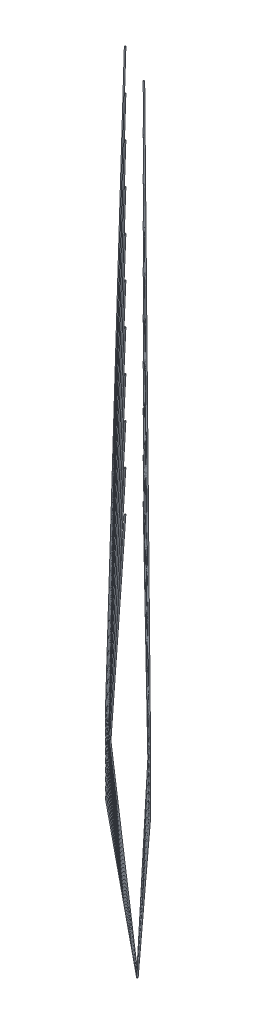
SolidWorks part; units mm, degrees
ref_plane "Front Plane" through (0, 0, 0) normal (0, 0, 1) x (1, 0, 0)
ref_plane "Top Plane" through (0, 0, 0) normal (0, 1, 0) x (1, 0, 0)
ref_plane "Right Plane" through (0, 0, 0) normal (1, 0, 0) x (0, 0, -1)
sketch3d "3DSketch1"
  line L0 (0, -235, 30) -> (-30, -45, 25)
  line L1 (-30, -45, 25) -> (-10, 300, 0)
sketch3d "3DSketch2"
  line L0 (0, -235, 30) -> (-30, -34, 25)
  line L1 (-30, -34, 25) -> (-10, 356, 0)
sketch3d "3DSketch3"
  line L0 (0, -235, 30) -> (-30, -23, 25)
  line L1 (-30, -23, 25) -> (-10, 412, 0)
sketch3d "3DSketch4"
  line L0 (0, -235, 30) -> (-30, -12, 25)
  line L1 (-30, -12, 25) -> (-10, 468, 0)
sketch3d "3DSketch5"
  line L0 (0, -235, 30) -> (-30, -1, 25)
  line L1 (-30, -1, 25) -> (-10, 524, 0)
sketch3d "3DSketch6"
  line L0 (0, -235, 30) -> (-30, 10, 25)
  line L1 (-30, 10, 25) -> (-10, 580, 0)
sketch3d "3DSketch7"
  line L0 (0, -235, 30) -> (-30, 21, 25)
  line L1 (-30, 21, 25) -> (-10, 636, 0)
sketch3d "3DSketch8"
  line L0 (0, -235, 30) -> (-30, 32, 25)
  line L1 (-30, 32, 25) -> (-10, 692, 0)
sketch3d "3DSketch9"
  line L0 (0, -235, 30) -> (-30, 43, 25)
  line L1 (-30, 43, 25) -> (-10, 748, 0)
sketch3d "3DSketch10"
  line L0 (0, -235, 30) -> (-30, 54, 25)
  line L1 (-30, 54, 25) -> (-10, 804, 0)
sketch3d "3DSketch11"
  line L0 (0, -235, 30) -> (-30, 65, 25)
  line L1 (-30, 65, 25) -> (-10, 860, 0)
sketch3d "3DSketch12"
  line L0 (0, -235, 30) -> (30, -39.5, 25)
  line L1 (30, -39.5, 25) -> (10, 328, 0)
sketch3d "3DSketch13"
  line L0 (0, -235, 30) -> (30, -28.5, 25)
  line L1 (30, -28.5, 25) -> (10, 384, 0)
sketch3d "3DSketch14"
  line L0 (0, -235, 30) -> (30, -17.5, 25)
  line L1 (30, -17.5, 25) -> (10, 440, 0)
sketch3d "3DSketch15"
  line L0 (0, -235, 30) -> (30, -6.5, 25)
  line L1 (30, -6.5, 25) -> (10, 496, 0)
sketch3d "3DSketch16"
  line L0 (0, -235, 30) -> (30, 4.5, 25)
  line L1 (30, 4.5, 25) -> (10, 552, 0)
sketch3d "3DSketch17"
  line L0 (0, -235, 30) -> (30, 15.5, 25)
  line L1 (30, 15.5, 25) -> (10, 608, 0)
sketch3d "3DSketch18"
  line L0 (0, -235, 30) -> (30, 26.5, 25)
  line L1 (30, 26.5, 25) -> (10, 664, 0)
sketch3d "3DSketch19"
  line L0 (0, -235, 30) -> (30, 37.5, 25)
  line L1 (30, 37.5, 25) -> (10, 720, 0)
sketch3d "3DSketch20"
  line L0 (0, -235, 30) -> (30, 48.5, 25)
  line L1 (30, 48.5, 25) -> (10, 776, 0)
sketch3d "3DSketch21"
  line L0 (0, -235, 30) -> (30, 59.5, 25)
  line L1 (30, 59.5, 25) -> (10, 832, 0)
sketch3d "3DSketch22"
  line L0 (0, -250, 12) -> (-30, -45, 25)
  line L1 (-30, -45, 25) -> (-13, 300, 16)
sweep "Sweep22" add path "3DSketch22" circular profile diameter 1.5 parameters "D3"=1.5
sketch3d "3DSketch23"
  line L0 (0, -250, 12) -> (-30, -34, 25)
  line L1 (-30, -34, 25) -> (-13, 356, 16)
sweep "Sweep23" add path "3DSketch23" circular profile diameter 1.5 parameters "D3"=1.5
sketch3d "3DSketch24"
  line L0 (0, -250, 12) -> (-30, -23, 25)
  line L1 (-30, -23, 25) -> (-13, 412, 16)
sweep "Sweep24" add path "3DSketch24" circular profile diameter 1.5 parameters "D3"=1.5
sketch3d "3DSketch25"
  line L0 (0, -250, 12) -> (-30, -12, 25)
  line L1 (-30, -12, 25) -> (-13, 468, 16)
sweep "Sweep25" add path "3DSketch25" circular profile diameter 1.5 parameters "D3"=1.5
sketch3d "3DSketch26"
  line L0 (0, -250, 12) -> (-30, -1, 25)
  line L1 (-30, -1, 25) -> (-13, 524, 16)
sweep "Sweep26" add path "3DSketch26" circular profile diameter 1.5 parameters "D3"=1.5
sketch3d "3DSketch27"
  line L0 (0, -250, 12) -> (-30, 10, 25)
  line L1 (-30, 10, 25) -> (-13, 580, 16)
sweep "Sweep27" add path "3DSketch27" circular profile diameter 1.5 parameters "D3"=1.5
sketch3d "3DSketch28"
  line L0 (0, -250, 12) -> (-30, 21, 25)
  line L1 (-30, 21, 25) -> (-13, 636, 16)
sweep "Sweep28" add path "3DSketch28" circular profile diameter 1.5 parameters "D3"=1.5
sketch3d "3DSketch29"
  line L0 (0, -250, 12) -> (-30, 32, 25)
  line L1 (-30, 32, 25) -> (-13, 692, 16)
sweep "Sweep29" add path "3DSketch29" circular profile diameter 1.5 parameters "D3"=1.5
sketch3d "3DSketch30"
  line L0 (0, -250, 12) -> (-30, 43, 25)
  line L1 (-30, 43, 25) -> (-13, 748, 16)
sweep "Sweep30" add path "3DSketch30" circular profile diameter 1.5 parameters "D3"=1.5
sketch3d "3DSketch31"
  line L0 (0, -250, 12) -> (-30, 54, 25)
  line L1 (-30, 54, 25) -> (-13, 804, 16)
sweep "Sweep31" add path "3DSketch31" circular profile diameter 1.5 parameters "D3"=1.5
sketch3d "3DSketch32"
  line L0 (0, -250, 12) -> (-30, 65, 25)
  line L1 (-30, 65, 25) -> (-13, 860, 16)
sweep "Sweep32" add path "3DSketch32" circular profile diameter 1.5 parameters "D3"=1.5
sketch3d "3DSketch33"
  line L0 (0, -250, 12) -> (30, -39.5, 25)
  line L1 (30, -39.5, 25) -> (13, 328, 16)
sweep "Sweep33" add path "3DSketch33" circular profile diameter 1.5 parameters "D3"=1.5
sketch3d "3DSketch34"
  line L0 (0, -250, 12) -> (30, -28.5, 25)
  line L1 (30, -28.5, 25) -> (13, 384, 16)
sweep "Sweep34" add path "3DSketch34" circular profile diameter 1.5 parameters "D3"=1.5
sketch3d "3DSketch35"
  line L0 (0, -250, 12) -> (30, -17.5, 25)
  line L1 (30, -17.5, 25) -> (13, 440, 16)
sweep "Sweep35" add path "3DSketch35" circular profile diameter 1.5 parameters "D3"=1.5
sketch3d "3DSketch36"
  line L0 (0, -250, 12) -> (30, -6.5, 25)
  line L1 (30, -6.5, 25) -> (13, 496, 16)
sweep "Sweep36" add path "3DSketch36" circular profile diameter 1.5 parameters "D3"=1.5
sketch3d "3DSketch37"
  line L0 (0, -250, 12) -> (30, 4.5, 25)
  line L1 (30, 4.5, 25) -> (13, 552, 16)
sweep "Sweep37" add path "3DSketch37" circular profile diameter 1.5 parameters "D3"=1.5
sketch3d "3DSketch38"
  line L0 (0, -250, 12) -> (30, 15.5, 25)
  line L1 (30, 15.5, 25) -> (13, 608, 16)
sweep "Sweep38" add path "3DSketch38" circular profile diameter 1.5 parameters "D3"=1.5
sketch3d "3DSketch39"
  line L0 (0, -250, 12) -> (30, 26.5, 25)
  line L1 (30, 26.5, 25) -> (13, 664, 16)
sweep "Sweep39" add path "3DSketch39" circular profile diameter 1.5 parameters "D3"=1.5
sketch3d "3DSketch40"
  line L0 (0, -250, 12) -> (30, 37.5, 25)
  line L1 (30, 37.5, 25) -> (13, 720, 16)
sweep "Sweep40" add path "3DSketch40" circular profile diameter 1.5 parameters "D3"=1.5
sketch3d "3DSketch41"
  line L0 (0, -250, 12) -> (30, 48.5, 25)
  line L1 (30, 48.5, 25) -> (13, 776, 16)
sweep "Sweep41" add path "3DSketch41" circular profile diameter 1.5 parameters "D3"=1.5
sketch3d "3DSketch42"
  line L0 (0, -250, 12) -> (30, 59.5, 25)
  line L1 (30, 59.5, 25) -> (13, 832, 16)
sweep "Sweep42" add path "3DSketch42" circular profile diameter 1.5 parameters "D3"=1.5
